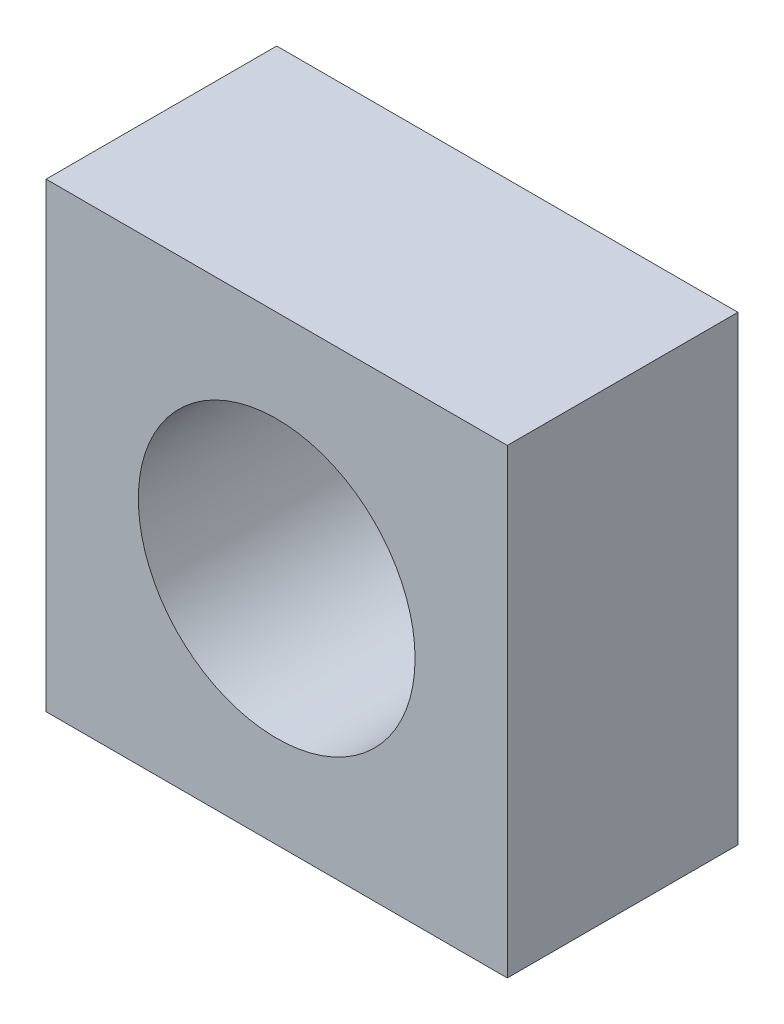
SolidWorks part; units mm, degrees
ref_plane "Front Plane" through (0, 0, 0) normal (0, 0, 1) x (1, 0, 0)
ref_plane "Top Plane" through (0, 0, 0) normal (0, 1, 0) x (1, 0, 0)
ref_plane "Right Plane" through (0, 0, 0) normal (1, 0, 0) x (0, 0, -1)
sketch "Sketch1" plane through (0, 0, 0) normal (0, 0, 1) x (1, 0, 0)
  line L1 (2.5, -2.5) -> (-2.5, -2.5)
  line L2 (2.5, -2.5) -> (2.5, 2.5)
  line L3 (2.5, 2.5) -> (-2.5, 2.5)
  line L4 (-2.5, -2.5) -> (-2.5, 2.5)
  line L5 (2.5, -2.5) -> (-2.5, 2.5) construction
  line L6 (2.5, 2.5) -> (-2.5, -2.5) construction
  circle A0 centre (0, 0) radius 1.5
  point P0 (0, 0)
  dimension "D1" = 5
  dimension "D2" = 5
extrude "Boss-Extrude1" add sketch "Sketch1" along normal blind 2.5
